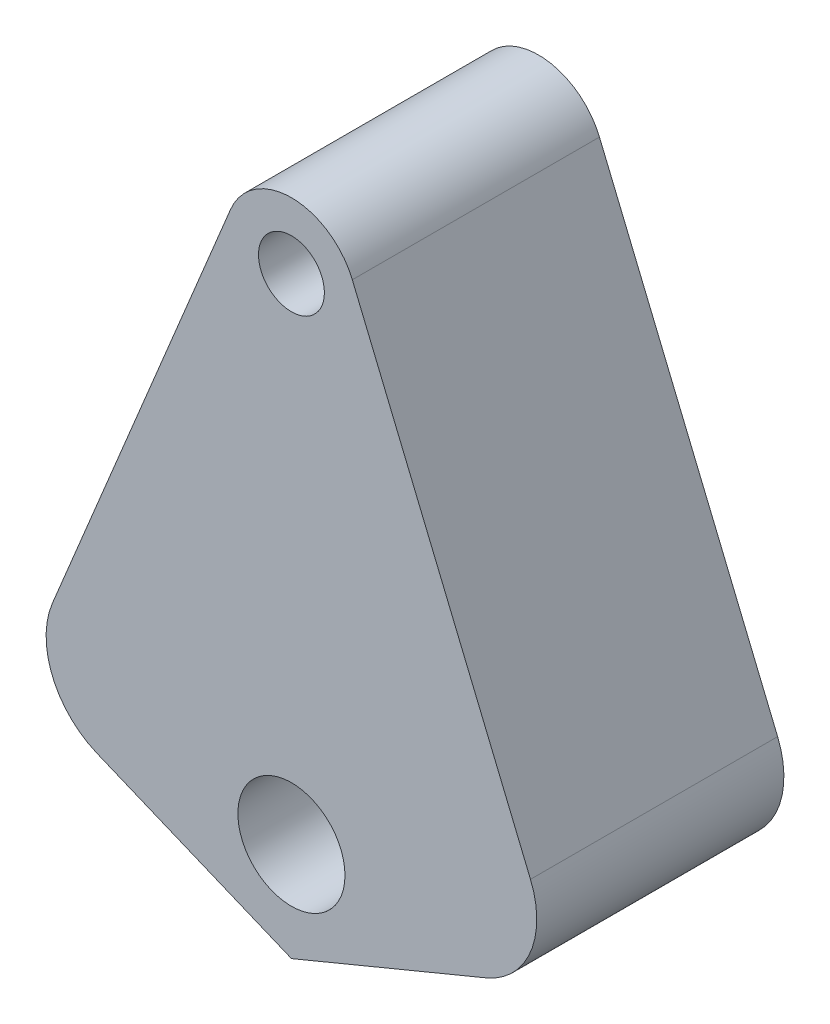
SolidWorks part; units mm, degrees
ref_plane "Front" through (0, 0, 0) normal (0, 0, 1) x (1, 0, 0)
ref_plane "Top" through (0, 0, 0) normal (0, 1, 0) x (1, 0, 0)
ref_plane "Right" through (0, 0, 0) normal (1, 0, 0) x (0, 0, -1)
sketch "Эскиз2" plane through (0, 0, 0) normal (0, 0, 1) x (1, 0, 0)
  line L0 (14.7821, -35.6871) -> (58.0401, -140.1212)
  line L1 (47.2162, -166.2524) -> (0, -185.81)
  line L2 (0, 41.1583) -> (0, -204.0131) construction
  line L3 (-47.2162, -166.2524) -> (0, -185.81)
  line L4 (-14.7821, -35.6871) -> (-58.0401, -140.1212)
  arc A0 (-47.2162, -166.2524) -> (-58.0401, -140.1212) centre (-39.5625, -147.7748) cw
  arc A1 (58.0401, -140.1212) -> (47.2162, -166.2524) centre (39.5625, -147.7748) cw
  arc A2 (14.7821, -35.6871) -> (-14.7821, -35.6871) centre (0, -41.81) ccw
  circle A3 centre (0, -41.81) radius 8
  circle A4 centre (0, -161.81) radius 13
  point P9 (-65.6938, -158.5988)
  point P12 (65.6938, -158.5988)
  point P15 (0, 0)
  dimension "D1" = 20
  dimension "D4" = 16
  dimension "D5" = 16
  dimension "D6" = 26
  dimension "D2" = 45
  dimension "D3" = 160
  dimension "D7" = 120
extrude "Бобышка-Вытянуть1" add sketch "Эскиз2" along normal mid plane 60
sketch "Эскиз4" plane through (0, 0, 0) normal (0, 0, 1) x (1, 0, 0)
  circle A0 centre (0, -185.81) radius 60
  point P2 (0, 0)
  dimension "D1" = 120
